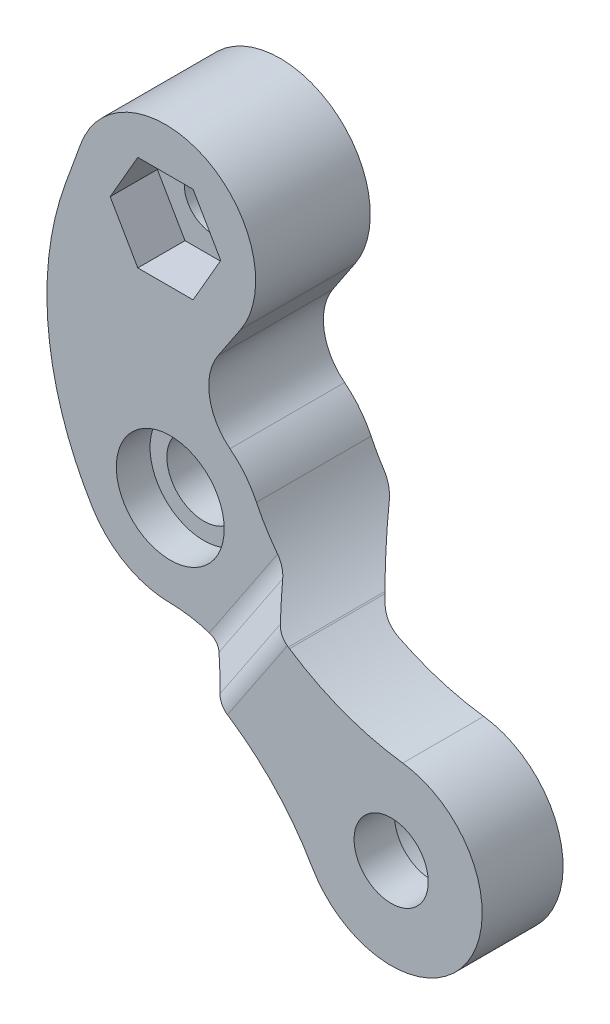
SolidWorks part; units mm, degrees
ref_plane "Front Plane" through (0, 0, 0) normal (0, 0, 1) x (1, 0, 0)
ref_plane "Top Plane" through (0, 0, 0) normal (0, 1, 0) x (1, 0, 0)
ref_plane "Right Plane" through (0, 0, 0) normal (1, 0, 0) x (0, 0, -1)
sketch "Sketch6" plane through (0, 0, 0) normal (0, 0, 1) x (1, 0, 0)
  line L0 (0, 0) -> (40.1809, 0) construction
  line L1 (0, 0) -> (35.507, 92.499) construction
  line L2 (19.3519, 50.4133) -> (0.4719, 63.0164) construction
  line L3 (19.3519, 50.4133) -> (-36.1025, 71.7003) construction
  dimension "D1" = 69
  dimension "D2" = 54
  dimension "D3" = 22.7
  dimension "D4" = 5
sketch "Sketch3" plane through (0, 0, 0) normal (0, 0, 1) x (1, 0, 0)
  line L0 (24.1743, 72.523) -> (120.8717, 72.523) construction
  line L6 (11.8164, 60.2529) -> (11.7284, 60.3116)
  line L7 (7.3748, 53.5992) -> (5.9136, 54.5745)
  line L8 (19.3519, 50.4133) -> (0.4719, 63.0164) construction
  line L9 (-6.1719, 82.4206) -> (-7.2903, 79.3479)
  line L10 (19.3519, 50.4133) -> (13.2479, 41.2693) construction
  line L11 (19.3519, 50.4133) -> (31.6629, 68.8558) construction
  line L12 (4.0204, 73.9337) -> (5.6789, 76.4182)
  line L14 (0.1147, 80.1325) -> (27.1455, 62.0885) construction
  line L15 (0.1147, 80.1325) -> (-7.2903, 79.3479) construction
  line L16 (0.1147, 80.1325) -> (0.1147, 91.1913) construction
  line L17 (0.1147, 80.1325) -> (-6.1719, 82.4206) construction
  arc A0 (13.4996, 47.0498) -> (20.2139, 57.1081) centre (19.3519, 50.4133) ccw
  arc A1 (20.2139, 57.1081) -> (11.8164, 60.2529) centre (22.7223, 76.5904) cw
  arc A2 (13.4996, 47.0498) -> (7.3748, 53.5992) centre (-3.5311, 37.2616) ccw
  arc A3 (11.7284, 60.3116) -> (6.8662, 65.9311) centre (19.4923, 71.9424) cw
  arc A4 (-6.1719, 82.4206) -> (5.6789, 76.4182) centre (0.1147, 80.1325) cw
  arc A5 (6.8662, 65.9311) -> (4.9012, 68.3908) centre (0.6246, 62.9595) ccw
  arc A6 (4.9012, 68.3908) -> (4.0204, 73.9337) centre (7.4585, 71.6386) cw
  arc A7 (5.9136, 54.5745) -> (0.4148, 56.2666) centre (0.3298, 46.2096) ccw
  arc A10 (0.4148, 56.2666) -> (-5.2798, 59.4837) centre (0.4719, 63.0164) cw
  circle A12 centre (19.3519, 50.4133) radius 2.75
  circle A13 centre (0.4719, 63.0164) radius 2.75
  circle A17 centre (0.1147, 80.1325) radius 2.1
  arc A18 (-7.2903, 79.3479) -> (-5.2798, 59.4837) centre (14.2795, 71.4971) ccw
  dimension "D1" = 5.5
  dimension "D2" = 5.5
  dimension "D3" = 4
  dimension "D5" = 4
  dimension "D6" = 4
  dimension "D4" = 4.2
  dimension "D17" = 70
  dimension "D18" = 3.27
  dimension "D14" = 6.69
  dimension "D7" = 3
  dimension "D8" = 4
  dimension "D9" = 3
  dimension "D10" = 4
  dimension "D11" = 19
  dimension "D12" = 19
  dimension "D13" = 22
  dimension "D15" = 32.5
  dimension "D16" = 14
extrude "Boss-Extrude2" add sketch "Sketch3" along normal blind 11
sketch "Sketch8" plane through (31.4653, 47.1365, 0) normal (0.5552, 0.8317, 0) x (0.8317, -0.5552, 0)
  line L0 (-23.6246, -11) -> (-14.8943, -11) construction
  line L1 (-28.1812, -8.5) -> (-53.4099, -8.5)
  line L2 (-29.1776, 0) -> (1.7369, 0)
  line L3 (-51.0843, -11) -> (-37.7043, -11) construction
  line L5 (-23.6246, -11) -> (-23.7304, -11) construction
  line L6 (-53.4099, -8.5) -> (-53.4099, -11)
  line L7 (-53.4099, -11) -> (-23.8179, -11)
  line L8 (-11.8943, 0) -> (-69.8351, 0) construction
  line L9 (-21.224, -5) -> (1.7369, -5)
  line L11 (-26.9676, -8.9379) -> (-24.9929, -10.5761)
  line L12 (1.7369, 0) -> (1.7369, -5)
  line L13 (-30.8943, -11) -> (-23.7304, -11) construction
  line L14 (-27.7027, -0.5321) -> (-23.1583, -4.3021)
  arc A4 (-28.1812, -8.5) -> (-26.9676, -8.9379) centre (-28.1812, -10.4008) cw
  arc A5 (-23.8179, -11) -> (-24.9929, -10.5761) centre (-23.8179, -9.1597) cw
  arc A6 (-29.1776, 0) -> (-27.7027, -0.5321) centre (-29.1776, -2.3099) cw
  arc A7 (-21.224, -5) -> (-23.1583, -4.3021) centre (-21.224, -1.9703) cw
  dimension "D1" = 2.5
  dimension "D2" = 5
  dimension "D3" = 6
extrude "Cut-Extrude3" cut sketch "Sketch8" against normal through all and the other way through all
sketch "Sketch9" plane through (0, 0, 5) normal (0, 0, -1) x (-1, 0, 0)
  circle A0 centre (-19.3519, 50.4133) radius 5
  dimension "D1" = 10
extrude "Cut-Extrude5" cut sketch "Sketch9" against normal blind 3 and the other way through all
sketch "Sketch10" plane through (0, 0, 0) normal (0, 0, -1) x (-1, 0, 0)
  circle A0 centre (-0.4719, 63.0164) radius 5
  dimension "D1" = 10
extrude "Cut-Extrude6" cut sketch "Sketch10" against normal blind 3
sketch "Sketch11" plane through (0, 0, 8.5) normal (0, 0, 1) x (1, 0, 0)
  circle A0 centre (0.4719, 63.0164) radius 4
  dimension "D1" = 8
extrude "Cut-Extrude7" cut sketch "Sketch11" against normal blind 2.5
sketch "Sketch12" plane through (0, 0, 0) normal (0, 0, -1) x (-1, 0, 0)
  line L0 (-0.1147, 80.1325) -> (0.7728, 78.2293) construction
  line L1 (3.6918, 81.9075) -> (4.5793, 80.0043)
  line L2 (-3.9212, 78.3575) -> (-3.0337, 76.4543)
  line L3 (-0.1147, 80.1325) -> (-0.1147, 76.0993) construction
  arc A0 (3.6918, 81.9075) -> (-3.9212, 78.3575) centre (-0.1147, 80.1325) ccw
  arc A1 (-3.0337, 76.4543) -> (4.5793, 80.0043) centre (0.7728, 78.2293) ccw
  point P3 (0.3291, 79.1809)
  dimension "D2" = 4.2
  dimension "D3" = 25
  dimension "D1" = 2.1
extrude "Cut-Extrude8" cut sketch "Sketch12" against normal blind 2
sketch "Sketch7" plane through (0, 0, 8.5) normal (0, 0, 1) x (1, 0, 0)
  line L1 (2.1643, 76.5825) -> (4.2139, 80.1325)
  line L2 (4.2139, 80.1325) -> (2.1643, 83.6825)
  line L3 (2.1643, 83.6825) -> (-1.9349, 83.6825)
  line L4 (-1.9349, 83.6825) -> (-3.9845, 80.1325)
  line L5 (-3.9845, 80.1325) -> (-1.9349, 76.5825)
  line L6 (-1.9349, 76.5825) -> (2.1643, 76.5825)
  circle A0 centre (0.1147, 80.1325) radius 3.55 construction
  dimension "D1" = 7.1
extrude "Cut-Extrude9" cut sketch "Sketch7" against normal offset from surface (3.5 mm away) 3 up to face at (-1.9853, 80.1325, 2)
